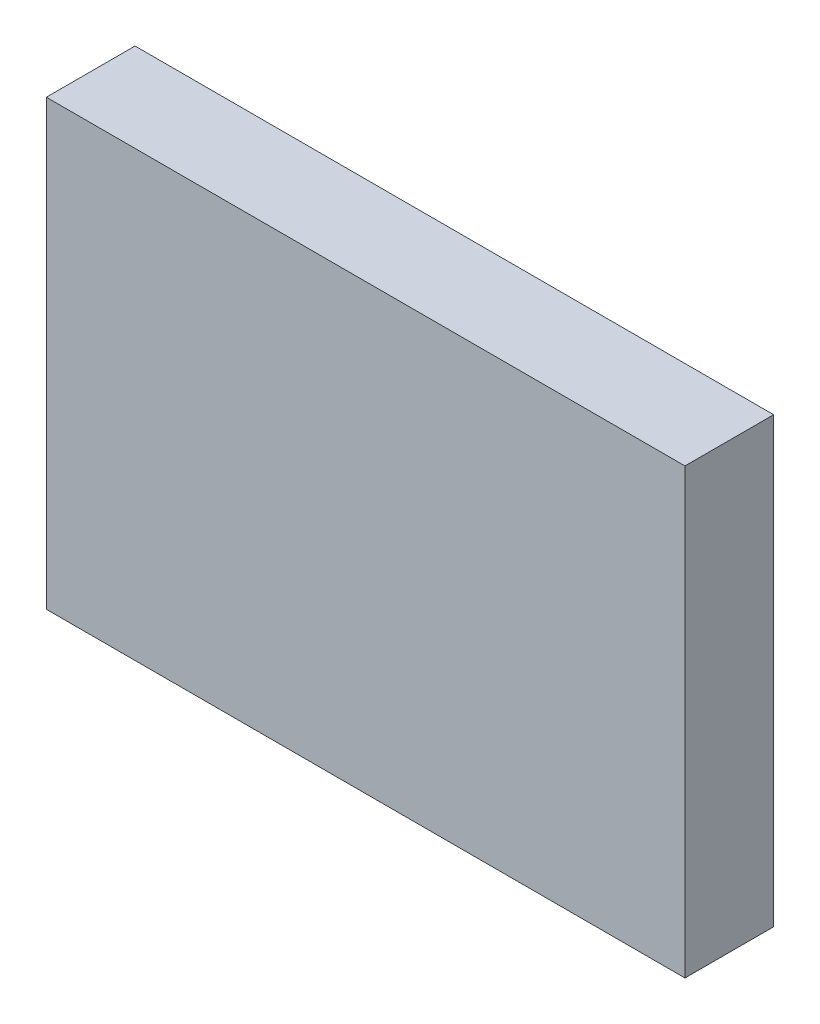
SolidWorks part; units mm, degrees
ref_plane "前视基准面" through (0, 0, 0) normal (0, 0, 1) x (1, 0, 0)
ref_plane "上视基准面" through (0, 0, 0) normal (0, 1, 0) x (1, 0, 0)
ref_plane "右视基准面" through (0, 0, 0) normal (1, 0, 0) x (0, 0, -1)
sketch "草图1" plane through (0, 0, 0) normal (0, 0, 1) x (1, 0, 0)
  line L1 (0, 0) -> (72, 0)
  line L2 (0, 0) -> (0, 50)
  line L3 (0, 50) -> (72, 50)
  line L4 (72, 0) -> (72, 50)
  dimension "D1" = 50
  dimension "D2" = 72
extrude "凸台-拉伸1" add sketch "草图1" along normal blind 10
